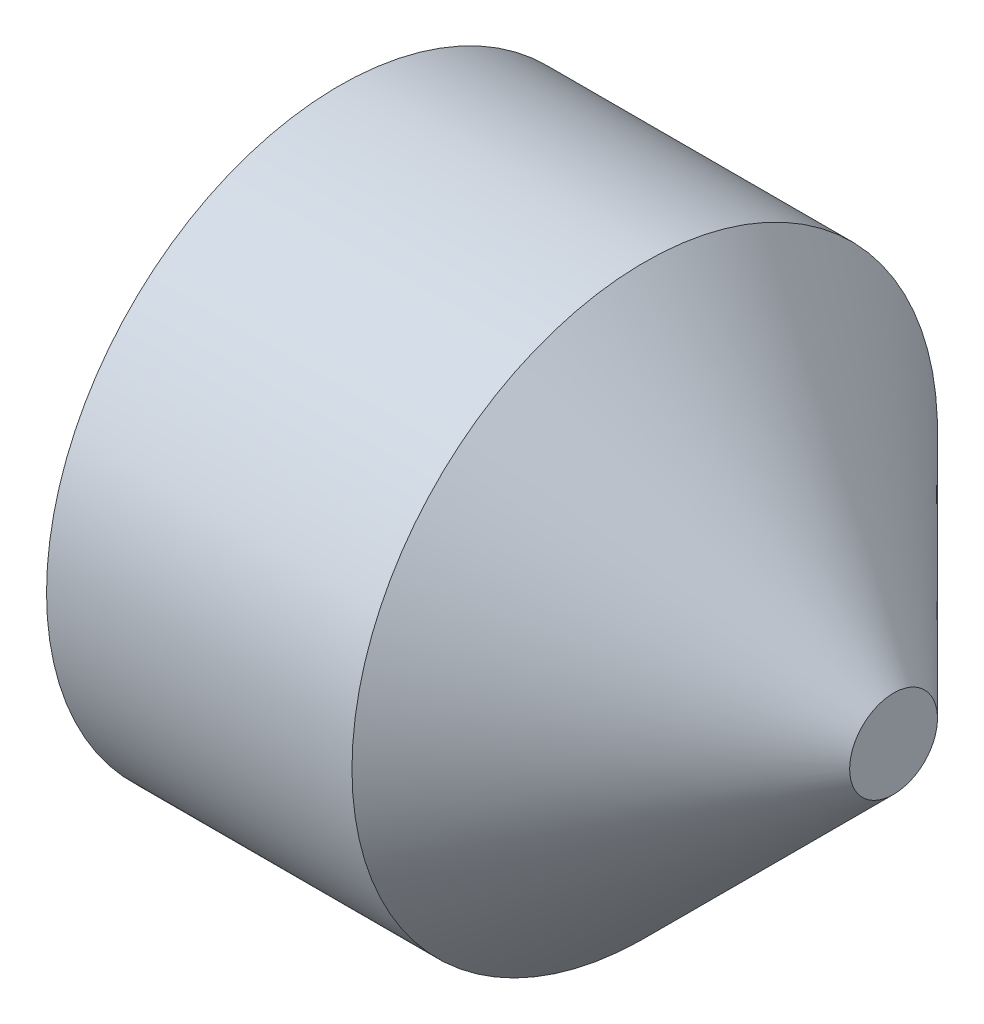
SolidWorks part; units mm, degrees
revolve "BaseBody" add sketch "BodySke" angle 360 about L5
sketch "BodySke" plane through (0, 0, 0) normal (0, 0, 1) x (1, 0, 0)
  line L0 (0, 0) -> (0, 2.4455)
  line L1 (0, 2.4455) -> (0.3201, 3)
  line L2 (0.3201, 3) -> (3.45, 3)
  line L3 (3.45, 3) -> (6, 0.45)
  line L4 (6, 0) -> (0, 0)
  line L5 (-12.7, 0) -> (88.9, 0) construction
  line L6 (6, 0.45) -> (6, 0)
  line L7 (6, 0.45) -> (6, 9.975) construction
  line L8 (0, -2.4455) -> (0.3201, -3) construction
  line L9 (1, 15.875) -> (1, -3.175) construction
  line L10 (3.45, -3) -> (6, -0.45) construction
  dimension "Diameter" = 6
  dimension "Drive_ch_ang" = 60
  dimension "Minor_dia" = 4.891
  dimension "Tip_dia" = 0.9
  dimension "Length" = 6
  dimension "Advance" = 1
  dimension "Cone_ang" = 90
cosmetic thread "ThreadCosmetic" [suppressed] parameters "Thread_minor"=4.891
material "Stahl verzinkt"
ref_plane "Plane1" through (0, 0, 0) normal (0, 0, 1) x (1, 0, 0)
ref_plane "Plane2" through (0, 0, 0) normal (0, 1, 0) x (1, 0, 0)
ref_plane "Plane3" through (0, 0, 0) normal (1, 0, 0) x (0, 0, -1)
sketch "Sketch2" plane through (0, 0, 0) normal (-1, 0, 0) x (0, 0, 1)
  line L0 (0.866, 1.5) -> (-0.866, 1.5)
  line L1 (-0.866, 1.5) -> (-1.7321, 0)
  line L2 (0.866, 1.5) -> (1.7321, 0)
  line L3 (0.866, -1.5) -> (1.7321, 0)
  line L4 (0.866, -1.5) -> (-0.866, -1.5)
  line L5 (-0.866, -1.5) -> (-1.7321, 0)
  dimension "Hex_size" = 3
  dimension "D2" = 1.5
  dimension "D3" = 1.5
extrude "Hex" cut sketch "Sketch2" against normal blind 3.5
sketch "ThdSchSke" [suppressed] plane through (0, 0, 0) normal (0, 0, 1) x (1, 0, 0)
  line L0 (0.9515, -10.352) -> (-0.2025, -12)
  line L1 (0.9515, -10.352) -> (2.1054, -12)
  line L2 (2.1054, -12) -> (2.1054, -15)
  line L3 (-3.175, 0) -> (5.1513, 0) construction
  line L5 (2.1054, -15) -> (-0.2025, -15)
  line L6 (-0.2025, -15) -> (-0.2025, -12)
  line L8 (0.9515, 12) -> (0.9515, -12) construction
  dimension "Thread_minor" = 4.891
  dimension "Diameter" = 6
revolve "ThreadSchematic" [suppressed] cut sketch "ThdSchSke" angle 360 about L3
pattern_linear "ThdSchPat" [suppressed]
equation "\"D2@Sketch2\" = \"Hex_size@Sketch2\" / 2"
equation "\"D3@Sketch2\" = \"Hex_size@Sketch2\" / 2"
equation "\"Thread_minor@ThreadCosmetic\" = \"Minor_dia@BodySke\""
equation "\"Thread_minor@ThdSchSke\" = \"Thread_minor@ThreadCosmetic\""
equation "\"Diameter@ThdSchSke\" = \"Diameter@BodySke\""
equation "\"Overcut@ThdSchSke\" = \"Diameter@BodySke\" * 1.25"
equation "\"Num_threads@ThdSchPat\" = int( (\"Length@BodySke\" - ( ( ( \"Diameter@BodySke\" - \"Minor_dia@BodySke\" ) * 0.5 ) / tan( \"Drive_ch_ang@BodySke\" * 0.017453292 ) ) - ( ( ( \"Diameter@BodySke\" - \"Tip_dia@BodySke\" ) * 0.5 ) / tan( \"Cone_ang@BodySke\" / 2.0 * 0.017453292 ) ) ) / \"Advance@BodySke\" + 0.999 )  + 1"
equation "\"Advance@ThdSchPat\" = (\"Length@BodySke\" - ( ( ( \"Diameter@BodySke\" - \"Minor_dia@BodySke\" ) * 0.5 ) / tan( \"Drive_ch_ang@BodySke\" * 0.017453292 ) ) - ( ( ( \"Diameter@BodySke\" - \"Tip_dia@BodySke\" ) * 0.5 ) / tan( \"Cone_ang@BodySke\" / 2.0 * 0.017453292 ) ) ) /  (\"Num_threads@ThdSchPat\" - 1) 'relax it"
equation "' \"Num_threads@ThdSchPat\" = \"Num_threads@ThdSchPat\" - sgn( \"Num_threads@ThdSchPat\" - 1) '---chamfered tips only---"
